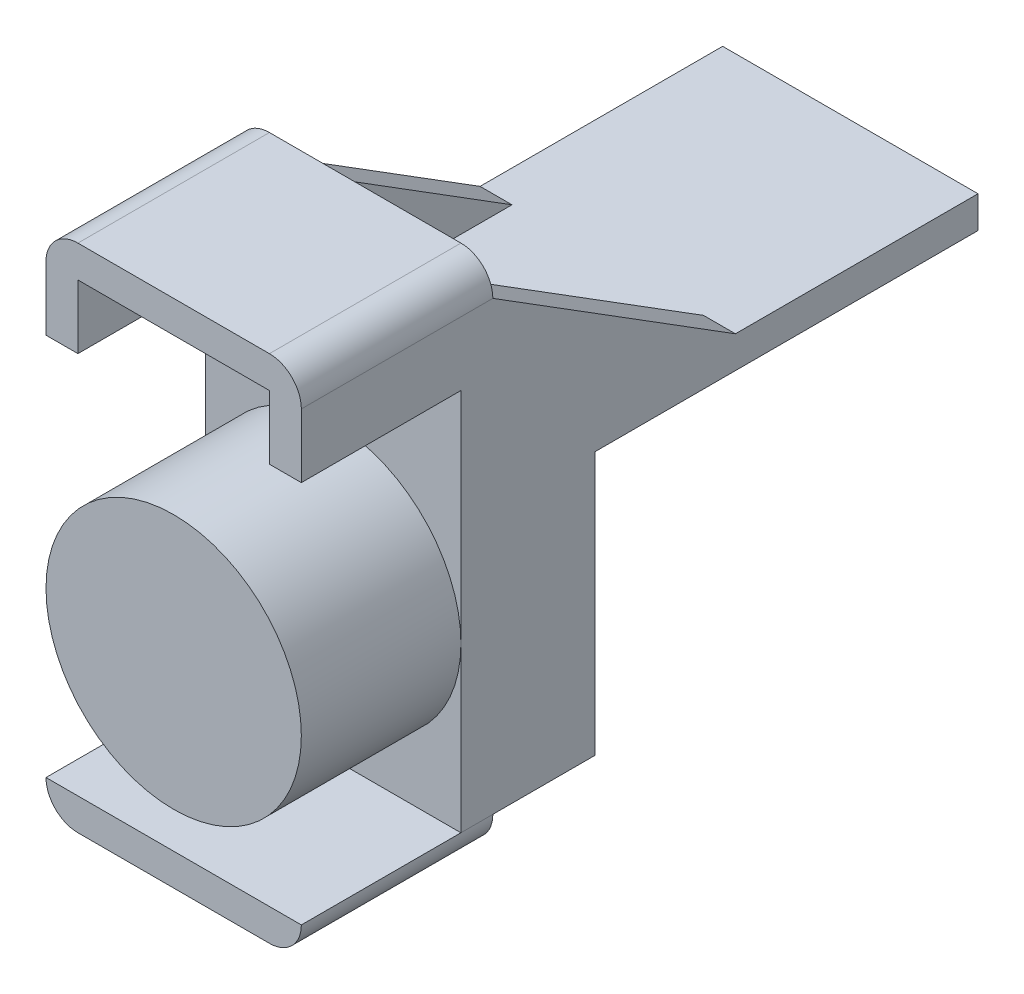
SolidWorks part; units mm, degrees
ref_plane "Ön Düzlem" through (0, 0, 0) normal (0, 0, 1) x (1, 0, 0)
ref_plane "Üst Düzlem" through (0, 0, 0) normal (0, 1, 0) x (1, 0, 0)
ref_plane "Sağ Düzlem" through (0, 0, 0) normal (1, 0, 0) x (0, 0, -1)
sketch "Çizim1" plane through (0, 0, 0) normal (0, 0, 1) x (1, 0, 0)
  line L0 (0, 0) -> (5, 0)
  line L1 (0, 0) -> (40, 0)
  line L2 (0, 0) -> (0, -80)
  line L3 (0, -80) -> (40, -80)
  line L4 (40, 0) -> (40, -80)
  line L5 (5, 0) -> (40, 0)
  line L6 (40, 0) -> (35, 0)
  line L7 (35, -80) -> (0, -80)
  line L8 (5, -5) -> (5, -75)
  line L9 (0, 0) -> (0, -5)
  line L10 (5, -5) -> (35, -5)
  line L11 (40, -5) -> (40, -80)
  line L12 (40, -80) -> (40, -75)
  line L13 (35, -75) -> (5, -75)
  line L14 (35, -5) -> (35, -75)
  line L15 (0, 0) -> (40, 0)
  line L16 (40, -80) -> (0, -80)
extrude "Yükseklik-Ekstrüzyon1" add sketch "Çizim1" along normal blind 30 contours L4 L5 L1 L0 L2 L3 L11 L10 L14 L13 L8
sketch "Çizim2" plane through (0, 0, 0) normal (0, 0, -1) x (-1, 0, 0)
  line L0 (-40, 0) -> (0, 0)
  line L1 (0, 0) -> (0, -80)
  line L2 (0, -80) -> (-40, -80)
  line L3 (-40, -80) -> (-40, 0)
extrude "Yükseklik-Ekstrüzyon2" add sketch "Çizim2" against normal blind 5
fillet "Radyus1" radius 5 1 edges at (40, 0, 15)
fillet "Radyus2" radius 5 1 edges at (0, 0, 15)
fillet "Radyus3" radius 5 1 edges at (0, -80, 15)
fillet "Radyus4" radius 5 1 edges at (40, -80, 15)
sketch "Çizim3" plane through (0, 0, 0) normal (0, 0, -1) x (-1, 0, 0)
  line L0 (-40, -5) -> (0, -5)
  line L1 (0, -5) -> (0, -75)
  line L2 (0, -75) -> (-40, -75)
  line L3 (-40, -75) -> (-40, -5)
  line L4 (-20, -5) -> (-20, -75)
  line L5 (-20, -75) -> (-20, -49.3296)
sketch "Çizim4" plane through (40, 0, 0) normal (1, 0, 0) x (0, 0, -1)
  line L0 (-30, -5) -> (0, -5)
  line L1 (0, -5) -> (0, -75)
  line L2 (0, -75) -> (-30, -75)
  line L3 (-30, -75) -> (-30, -5)
  line L4 (-30, -5) -> (0, -5)
  line L5 (-15, -5) -> (-15, -75)
  line L6 (-15, -75) -> (-15, -65)
  line L7 (-15, -65) -> (-30, -65)
  line L8 (-30, -65) -> (-5, -65)
  line L9 (-30, -5) -> (-30, -15)
  line L10 (-30, -15) -> (-5, -15)
  line L12 (-5, -15) -> (-5, -65)
extrude "Kes-Ekstrüzyon1" cut sketch "Çizim4" against normal blind 59 contours L10 L3 L7 L5 | L12 L10 L5 L8
sketch "Çizim5" plane through (0, 0, 0) normal (0, 0, -1) x (-1, 0, 0)
  circle A0 centre (-20, -49.3296) radius 20
extrude "Yükseklik-Ekstrüzyon4" add sketch "Çizim5" against normal blind 30
sketch "Çizim6" plane through (40, 0, 0) normal (1, 0, 0) x (0, 0, -1)
  line L0 (-5, -65) -> (-5, -75)
  line L1 (-30, -75) -> (0, -75) construction
  line L2 (-5, -75) -> (-30, -75)
  line L3 (-30, -75) -> (-30, -65)
  line L4 (-30, -65) -> (-30, -75) construction
  line L5 (-30, -29.3296) -> (-30, -69.3296) construction
  line L6 (-30, -65) -> (-5, -65)
extrude "Kes-Ekstrüzyon4" cut sketch "Çizim6" against normal blind 7
sketch "Çizim7" plane through (0, 0, 0) normal (-1, 0, 0) x (0, 0, 1)
  line L0 (30, -65) -> (30, -75)
  line L1 (30, -75) -> (30, -65)
  line L2 (0, -65) -> (30, -65)
  line L3 (0, -5) -> (0, -75) construction
  line L4 (0, -65) -> (0, -75)
  line L5 (0, -75) -> (0, -80) construction
  line L6 (0, -75) -> (30, -75)
  line L7 (5, -65) -> (5, -75)
  line M8 (30, -75) -> (30, -65)
  line M9 (30, -65) -> (5, -65)
extrude "Kes-Ekstrüzyon6" cut sketch "Çizim7" against normal blind 7 contours L7 L6 M9 M8
sketch "Çizim8" plane through (0, 0, 0) normal (0, 0, -1) x (-1, 0, 0)
sketch "Çizim12" plane through (0, 0, 0) normal (0, 0, -1) x (-1, 0, 0)
  line L0 (-40, -5) -> (0, -5)
  line L1 (0, -5) -> (0, 0)
  line L2 (0, 0) -> (-40, 0)
  line L3 (-40, 0) -> (-40, -5)
  line L4 (-35.2591, -28.8044) -> (0, -28.8044)
  line L5 (0, -5) -> (0, -75) construction
  line L6 (0, -28.8044) -> (-40, -28.8044)
  line L7 (-40, -75) -> (-40, -5) construction
  line L8 (-40, -28.8044) -> (-40, -33.8044)
  line L9 (-35, -33.8044) -> (-5, -33.8044)
  line L10 (0, -33.8044) -> (0, -28.8044)
  line L11 (0, -28.8044) -> (-5, -28.8044)
  line L12 (-5, -33.8044) -> (-5, -75)
  line L13 (0, -75) -> (-40, -75) construction
  line L14 (-5, -75) -> (0, -75)
  line L15 (0, -75) -> (0, -28.8044)
  line L16 (-40, -28.8044) -> (-35, -28.8044)
  line L17 (-35, -33.8044) -> (-35, -75)
  line L18 (-35, -75) -> (-40, -75)
  line L19 (-40, -75) -> (-40, -28.8044)
  line M6 (0, -75) -> (0, -5)
  line M10 (-40, -5) -> (-40, -75)
extrude "Yükseklik-Ekstrüzyon5" add sketch "Çizim12" along normal blind 16 contours L18 L17 L9 L12 L14 L6 L4 M6 M10
sketch "Çizim13" plane through (0, 0, -16) normal (0, 0, -1) x (-1, 0, 0)
  line L0 (-40, -28.8044) -> (0, -28.8044)
  line L1 (0, -28.8044) -> (0, -33.8044)
  line L2 (0, -5) -> (0, -75) construction
  line L3 (0, -33.8044) -> (-40, -33.8044)
  line L4 (-40, -75) -> (-40, -5) construction
  line L5 (-40, -33.8044) -> (-40, -28.8044)
extrude "Yükseklik-Ekstrüzyon6" add sketch "Çizim13" along normal blind 60
sketch "Çizim14" plane through (40, 0, 0) normal (1, 0, 0) x (0, 0, -1)
  line L0 (0, -5) -> (38, -28.8044)
  line L1 (76, -28.8044) -> (0, -28.8044) construction
  line L2 (38, -28.8044) -> (0, -28.8044)
  line L3 (0, -28.8044) -> (0, -5)
extrude "Yükseklik-Ekstrüzyon7" add sketch "Çizim14" against normal blind 5
sketch "Çizim15" plane through (0, 0, 0) normal (-1, 0, 0) x (0, 0, 1)
  line L0 (-38, -28.8044) -> (0, -5)
  line L1 (-76, -28.8044) -> (0, -28.8044) construction
  line L2 (0, -5) -> (0, -28.8044)
  line L3 (0, -28.8044) -> (-38, -28.8044)
extrude "Yükseklik-Ekstrüzyon8" add sketch "Çizim15" against normal blind 5
